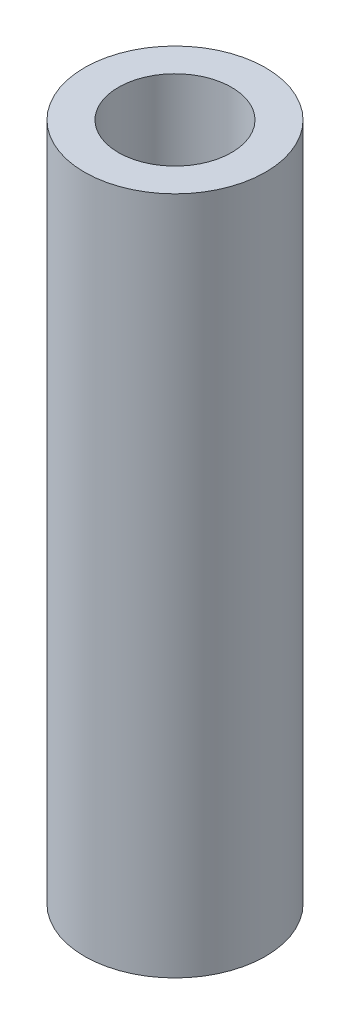
SolidWorks part; units mm, degrees
material "铬红铜，UNS C18200"
ref_plane "前视基准面" through (0, 0, 0) normal (0, 0, 1) x (1, 0, 0)
ref_plane "上视基准面" through (0, 0, 0) normal (0, 1, 0) x (1, 0, 0)
ref_plane "右视基准面" through (0, 0, 0) normal (1, 0, 0) x (0, 0, -1)
other "Configuration Table"
sketch "草图1" plane through (0, 0, 0) normal (0, 1, 0) x (1, 0, 0)
  circle A0 centre (0, 0) radius 2
  circle A1 centre (0, 0) radius 1.25
  dimension "D1" = 4
  dimension "D2" = 2.5
extrude "凸台-拉伸1" add sketch "草图1" along normal blind 15
